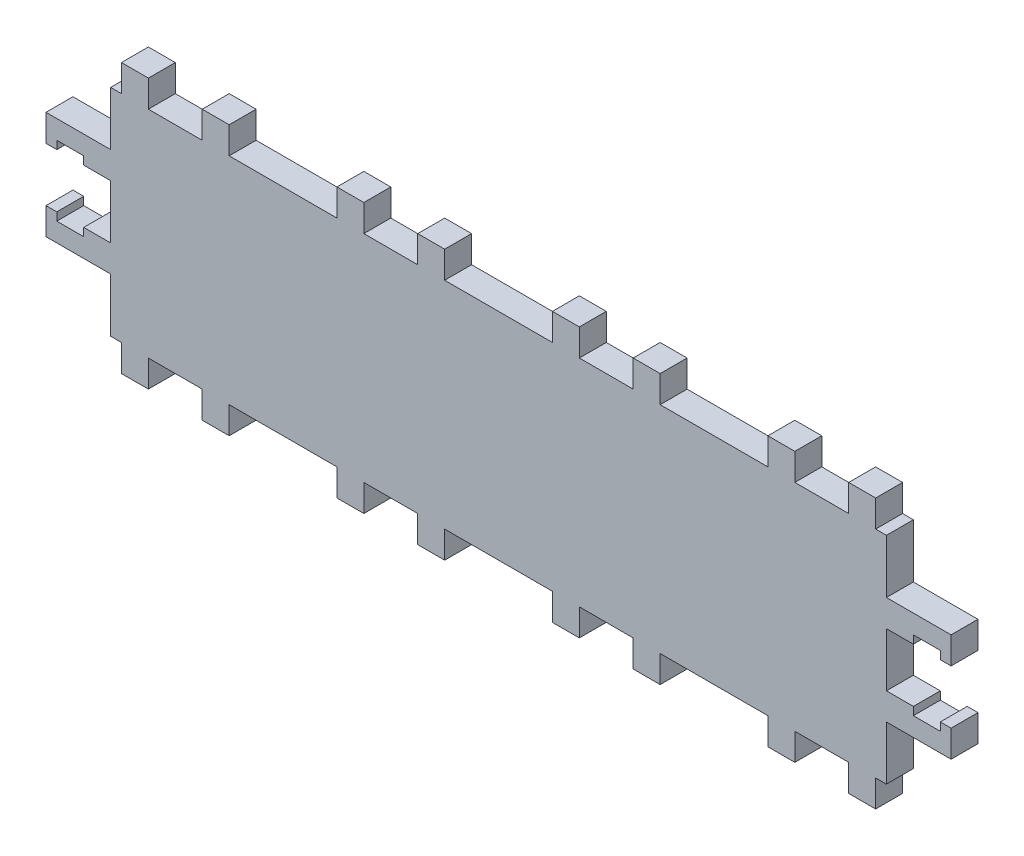
SolidWorks part; units mm, degrees
ref_plane "Plan de face" through (0, 0, 0) normal (0, 0, 1) x (1, 0, 0)
ref_plane "Plan de dessus" through (0, 0, 0) normal (0, 1, 0) x (1, 0, 0)
ref_plane "Plan de droite" through (0, 0, 0) normal (1, 0, 0) x (0, 0, -1)
sketch "Esquisse1" plane through (0, 0, 0) normal (0, 0, 1) x (1, 0, 0)
  line L0 (0, 0) -> (0, 20) construction
  line L1 (-27.1299, 20) -> (22.3044, 20) construction
  line L3 (-72, 40) -> (-72, 0) construction
  line L4 (-72, 0) -> (-70, 0)
  line L5 (70, 0) -> (72, 0)
  line L6 (-50, 40) -> (-30, 40)
  line L9 (50, 40) -> (30, 40)
  line L10 (10, 40) -> (-10, 40)
  line L11 (10, 0) -> (-10, 0)
  line L12 (50, 0) -> (30, 0)
  line L13 (-50, 0) -> (-30, 0)
  line L18 (-72, 0) -> (-72, 10)
  line L19 (-72, 30) -> (-72, 40)
  line L21 (72, 30) -> (72, 40)
  line L22 (72, 0) -> (72, 10)
  line L27 (70, 40) -> (72, 40)
  line L28 (-72, 40) -> (-70, 40)
  point P9 (-72, 151.4961)
  point P13 (72, 1.2386)
  point P15 (-72, 6.7088)
  line B0 (-60, 0) -> (-60, 11.1075) construction
  line B1 (-60, 0) -> (-65, 0)
  line B2 (-65, -5) -> (-70, -5)
  line B3 (-70, -5) -> (-70, 0)
  line B4 (-65, -5) -> (-65, 0)
  line B5 (-60, 0) -> (-55, 0)
  line B6 (-55, 0) -> (-55, -5)
  line B7 (-55, -5) -> (-50, -5)
  line B8 (-50, -5) -> (-50, 0)
  line B9 (-20, 0) -> (-20, 11.1075) construction
  line B10 (-20, 0) -> (-25, 0)
  line B11 (-25, -5) -> (-30, -5)
  line B12 (-30, -5) -> (-30, 0)
  line B13 (-25, -5) -> (-25, 0)
  line B14 (-20, 0) -> (-15, 0)
  line B15 (-15, 0) -> (-15, -5)
  line B16 (-15, -5) -> (-10, -5)
  line B17 (-10, -5) -> (-10, 0)
  line B18 (60, 0) -> (60, 11.1075) construction
  line B19 (60, 0) -> (65, 0)
  line B20 (65, -5) -> (70, -5)
  line B21 (70, -5) -> (70, 0)
  line B22 (65, -5) -> (65, 0)
  line B23 (60, 0) -> (55, 0)
  line B24 (55, 0) -> (55, -5)
  line B25 (55, -5) -> (50, -5)
  line B26 (50, -5) -> (50, 0)
  line B27 (72, 20) -> (60.135, 20) construction
  line B28 (72, 20) -> (72, 15)
  line B29 (77, 15) -> (77, 10) construction
  line B30 (77, 10) -> (72, 10)
  line B31 (77, 15) -> (72, 15)
  line B32 (72, 20) -> (72, 25)
  line B33 (72, 25) -> (77, 25)
  line B34 (77, 25) -> (77, 30) construction
  line B35 (77, 30) -> (72, 30)
  line B36 (77, 10) -> (84, 10)
  line B37 (84, 10) -> (84, 15)
  line B38 (84, 15) -> (82, 15)
  line B39 (82, 15) -> (82, 13.5)
  line B40 (82, 13.5) -> (77, 13.5)
  line B41 (77, 13.5) -> (77, 15)
  line B42 (82, 25) -> (82, 26.5)
  line B43 (84, 30) -> (84, 25)
  line B44 (84, 25) -> (82, 25)
  line B45 (82, 26.5) -> (77, 26.5)
  line B46 (77, 30) -> (84, 30)
  line B47 (77, 30) -> (72, 30)
  line B48 (77, 25) -> (77, 26.5)
  line B49 (-72, 20) -> (-60.135, 20) construction
  line B50 (-72, 20) -> (-72, 15)
  line B51 (-77, 15) -> (-77, 10) construction
  line B52 (-77, 10) -> (-72, 10)
  line B53 (-77, 15) -> (-72, 15)
  line B54 (-72, 20) -> (-72, 25)
  line B55 (-72, 25) -> (-77, 25)
  line B56 (-77, 25) -> (-77, 30) construction
  line B57 (-77, 30) -> (-72, 30)
  line B58 (-77, 10) -> (-84, 10)
  line B59 (-84, 10) -> (-84, 15)
  line B60 (-84, 15) -> (-82, 15)
  line B61 (-82, 15) -> (-82, 13.5)
  line B62 (-82, 13.5) -> (-77, 13.5)
  line B63 (-77, 13.5) -> (-77, 15)
  line B64 (-82, 25) -> (-82, 26.5)
  line B65 (-84, 30) -> (-84, 25)
  line B66 (-84, 25) -> (-82, 25)
  line B67 (-82, 26.5) -> (-77, 26.5)
  line B68 (-77, 30) -> (-84, 30)
  line B69 (-77, 30) -> (-72, 30)
  line B70 (-77, 25) -> (-77, 26.5)
  line B71 (20, 0) -> (20, 11.1075) construction
  line B72 (20, 0) -> (25, 0)
  line B73 (25, -5) -> (30, -5)
  line B74 (30, -5) -> (30, 0)
  line B75 (25, -5) -> (25, 0)
  line B76 (20, 0) -> (15, 0)
  line B77 (15, 0) -> (15, -5)
  line B78 (15, -5) -> (10, -5)
  line B79 (10, -5) -> (10, 0)
  line B80 (20, 40) -> (20, 28.8925) construction
  line B81 (20, 40) -> (25, 40)
  line B82 (25, 45) -> (30, 45)
  line B83 (30, 45) -> (30, 40)
  line B84 (25, 45) -> (25, 40)
  line B85 (20, 40) -> (15, 40)
  line B86 (15, 40) -> (15, 45)
  line B87 (15, 45) -> (10, 45)
  line B88 (10, 45) -> (10, 40)
  line B89 (-60, 40) -> (-60, 28.8925) construction
  line B90 (-60, 40) -> (-65, 40)
  line B91 (-65, 45) -> (-70, 45)
  line B92 (-70, 45) -> (-70, 40)
  line B93 (-65, 45) -> (-65, 40)
  line B94 (-60, 40) -> (-55, 40)
  line B95 (-55, 40) -> (-55, 45)
  line B96 (-55, 45) -> (-50, 45)
  line B97 (-50, 45) -> (-50, 40)
  line B98 (-20, 40) -> (-20, 28.8925) construction
  line B99 (-20, 40) -> (-25, 40)
  line B100 (-25, 45) -> (-30, 45)
  line B101 (-30, 45) -> (-30, 40)
  line B102 (-25, 45) -> (-25, 40)
  line B103 (-20, 40) -> (-15, 40)
  line B104 (-15, 40) -> (-15, 45)
  line B105 (-15, 45) -> (-10, 45)
  line B106 (-10, 45) -> (-10, 40)
  line B107 (60, 40) -> (60, 28.8925) construction
  line B108 (60, 40) -> (65, 40)
  line B109 (65, 45) -> (70, 45)
  line B110 (70, 45) -> (70, 40)
  line B111 (65, 45) -> (65, 40)
  line B112 (60, 40) -> (55, 40)
  line B113 (55, 40) -> (55, 45)
  line B114 (55, 45) -> (50, 45)
  line B115 (50, 45) -> (50, 40)
  dimension "D1" = 40
  dimension "D2" = 144
  dimension "D3" = 20
  dimension "D4" = 40
  dimension "D8" = 40
  dimension "D9" = 144
  dimension "D10" = 40
  dimension "D11" = 20
sketch_block_instance "Insert M3 plots ep 5mm-9"
sketch_block "Insert M3 plots ep 5mm" parameters "D1"=10, "D2"=5, "D3"=5
sketch_block_instance "Insert M3 plots ep 5mm-11"
sketch_block_instance "Insert M3 plots ep 5mm-12"
sketch_block_instance "Insert plots ep 5mm avec ergots-1"
sketch_block "Insert plots ep 5mm avec ergots" parameters "D1"=10, "D2"=5, "D3"=5, "D4"=5, "D5"=2, "D6"=1.5, "D7"=2, "D8"=2, "D9"=2.0716, "D10"=2
sketch_block_instance "Insert plots ep 5mm avec ergots-3"
sketch_block_instance "Insert M3 plots ep 5mm-24"
sketch_block_instance "Insert M3 plots ep 5mm-25"
sketch_block_instance "Insert M3 plots ep 5mm-26"
sketch_block_instance "Insert M3 plots ep 5mm-27"
sketch_block_instance "Insert M3 plots ep 5mm-28"
extrude "Boss.-Extru.1" add sketch "Esquisse1" along normal blind 5
